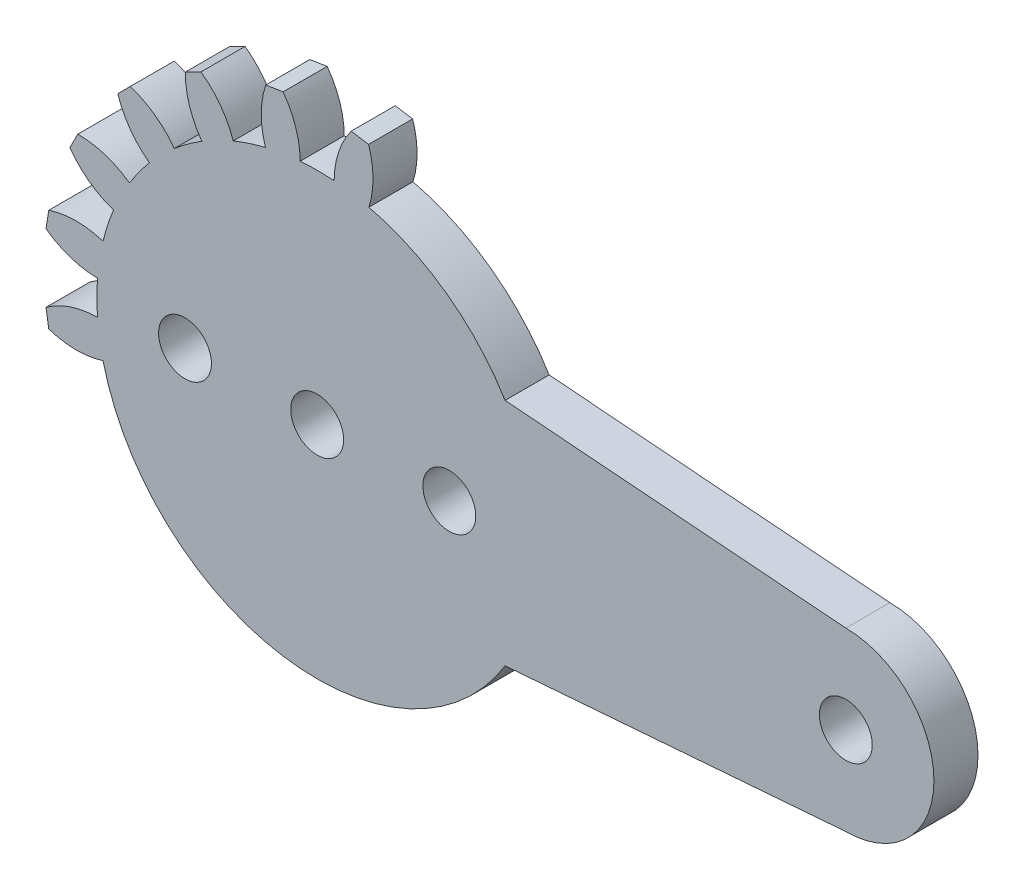
SolidWorks part; units mm, degrees
ref_plane "Front Plane" through (0, 0, 0) normal (0, 0, 1) x (1, 0, 0)
ref_plane "Top Plane" through (0, 0, 0) normal (0, 1, 0) x (1, 0, 0)
ref_plane "Right Plane" through (0, 0, 0) normal (1, 0, 0) x (0, 0, -1)
sketch "Sketch1" plane through (0, 0, 0) normal (0, 0, 1) x (1, 0, 0)
  line L0 (0, 0) -> (30, 0) construction
  line L1 (30, 5) -> (10.6638, 6.5218)
  line L2 (10.6638, 6.5218) -> (-2.4545, 7.5542) construction
  line L3 (-9.5123, 8.1097) -> (-9.5263, 8.1108) construction
  line L4 (30, -5) -> (10.6638, -6.5218)
  line L5 (0, 0) -> (-12.5, 0) construction
  line L6 (0, 0) -> (0, -12.5) construction
  line L7 (0, 0) -> (-4.7898, 14.7414) construction
  line L8 (0, 0) -> (0, 14) construction
  line L9 (0, 0) -> (-2.4247, 15.3092) construction
  line L10 (-2.9186, 15.231) -> (-1.9309, 15.3874)
  line L11 (1.9309, 15.3874) -> (2.9186, 15.231)
  line L12 (6.5913, 14.0376) -> (7.4824, 13.5836) [skipped]
  line L13 (10.6066, 11.3137) -> (11.3137, 10.6066) [skipped]
  line L14 (13.5836, 7.4824) -> (14.0376, 6.5913) [skipped]
  line L15 (15.231, 2.9186) -> (15.3874, 1.9309) [skipped]
  line L16 (15.3874, -1.9309) -> (15.231, -2.9186) [skipped]
  line L17 (14.0376, -6.5913) -> (13.5836, -7.4824) [skipped]
  line L18 (11.3137, -10.6066) -> (10.6066, -11.3137) [skipped]
  line L19 (7.4824, -13.5836) -> (6.5913, -14.0376) [skipped]
  line L20 (2.9186, -15.231) -> (1.9309, -15.3874) [skipped]
  line L21 (-1.9309, -15.3874) -> (-2.9186, -15.231) [skipped]
  line L22 (-6.5913, -14.0376) -> (-7.4824, -13.5836) [skipped]
  line L23 (-10.6066, -11.3137) -> (-11.3137, -10.6066) [skipped]
  line L24 (-13.5836, -7.4824) -> (-14.0376, -6.5913) [skipped]
  line L25 (-15.231, -2.9186) -> (-15.3874, -1.9309)
  line L26 (-15.3874, 1.9309) -> (-15.231, 2.9186)
  line L27 (-14.0376, 6.5913) -> (-13.5836, 7.4824)
  line L28 (-11.3137, 10.6066) -> (-10.6066, 11.3137)
  line L29 (-7.4824, 13.5836) -> (-6.5913, 14.0376)
  line L30 (-2.4545, 7.5542) -> (-9.5123, 8.1097) construction
  line L31 (-9.5263, 8.1108) -> (-11.3101, 8.2512) construction
  line L32 (-11.3101, 8.2512) -> (-26.6541, 9.4588) construction
  arc A0 (-12.1503, -2.9361) -> (10.6638, -6.5218) centre (0, 0) ccw
  circle A1 centre (30, 0) radius 1.5
  circle A2 centre (0, 0) radius 1.5
  arc A3 (30, -5) -> (30, 5) centre (30, 0) ccw
  circle A4 centre (-7.5, 0) radius 1.5
  circle A5 centre (7.5, 0) radius 1.5
  arc A6 (-15.3799, -1.9254) -> (-15.3799, 1.9254) centre (0, 0) ccw construction
  arc A7 (-10.5802, 9.1684) -> (-11.3101, 8.2512) centre (0, 0) ccw construction
  arc A8 (-2.9361, 12.1503) -> (-2.9186, 15.231) centre (1.8294, 13.6636) cw
  arc A9 (-0.9623, 12.4629) -> (-1.9309, 15.3874) centre (-5.9622, 12.4295) ccw
  arc A10 (2.9361, 12.1503) -> (2.9186, 15.231) centre (-1.8294, 13.6636) ccw
  arc A11 (0.9623, 12.4629) -> (1.9309, 15.3874) centre (5.9622, 12.4295) cw
  arc A12 (6.547, 10.6483) -> (7.4824, 13.5836) centre (2.4824, 13.5602) ccw [skipped]
  arc A13 (4.7664, 11.5556) -> (6.5913, 14.0376) centre (9.5113, 9.9788) cw [skipped]
  arc A14 (9.5171, 8.104) -> (11.3137, 10.6066) centre (6.5512, 12.1294) ccw [skipped]
  arc A15 (8.104, 9.5171) -> (10.6066, 11.3137) centre (12.1294, 6.5512) cw [skipped]
  arc A16 (11.5556, 4.7664) -> (14.0376, 6.5913) centre (9.9788, 9.5113) ccw [skipped]
  arc A17 (10.6483, 6.547) -> (13.5836, 7.4824) centre (13.5602, 2.4824) cw [skipped]
  arc A18 (12.4629, 0.9623) -> (15.3874, 1.9309) centre (12.4295, 5.9622) ccw [skipped]
  arc A19 (12.1503, 2.9361) -> (15.231, 2.9186) centre (13.6636, -1.8294) cw [skipped]
  arc A20 (12.1503, -2.9361) -> (15.231, -2.9186) centre (13.6636, 1.8294) ccw [skipped]
  arc A21 (12.4629, -0.9623) -> (15.3874, -1.9309) centre (12.4295, -5.9622) cw [skipped]
  arc A22 (10.6483, -6.547) -> (13.5836, -7.4824) centre (13.5602, -2.4824) ccw [skipped]
  arc A23 (11.5556, -4.7664) -> (14.0376, -6.5913) centre (9.9788, -9.5113) cw [skipped]
  arc A24 (8.104, -9.5171) -> (10.6066, -11.3137) centre (12.1294, -6.5512) ccw [skipped]
  arc A25 (9.5171, -8.104) -> (11.3137, -10.6066) centre (6.5512, -12.1294) cw [skipped]
  arc A26 (4.7664, -11.5556) -> (6.5913, -14.0376) centre (9.5113, -9.9788) ccw [skipped]
  arc A27 (6.547, -10.6483) -> (7.4824, -13.5836) centre (2.4824, -13.5602) cw [skipped]
  arc A28 (0.9623, -12.4629) -> (1.9309, -15.3874) centre (5.9622, -12.4295) ccw [skipped]
  arc A29 (2.9361, -12.1503) -> (2.9186, -15.231) centre (-1.8294, -13.6636) cw [skipped]
  arc A30 (-2.9361, -12.1503) -> (-2.9186, -15.231) centre (1.8294, -13.6636) ccw [skipped]
  arc A31 (-0.9623, -12.4629) -> (-1.9309, -15.3874) centre (-5.9622, -12.4295) cw [skipped]
  arc A32 (-6.547, -10.6483) -> (-7.4824, -13.5836) centre (-2.4824, -13.5602) ccw [skipped]
  arc A33 (-4.7664, -11.5556) -> (-6.5913, -14.0376) centre (-9.5113, -9.9788) cw [skipped]
  arc A34 (-9.5171, -8.104) -> (-11.3137, -10.6066) centre (-6.5512, -12.1294) ccw [skipped]
  arc A35 (-8.104, -9.5171) -> (-10.6066, -11.3137) centre (-12.1294, -6.5512) cw [skipped]
  arc A36 (-11.5556, -4.7664) -> (-14.0376, -6.5913) centre (-9.9788, -9.5113) ccw [skipped]
  arc A37 (-10.6483, -6.547) -> (-13.5836, -7.4824) centre (-13.5602, -2.4824) cw [skipped]
  arc A38 (-12.4629, -0.9623) -> (-15.3874, -1.9309) centre (-12.4295, -5.9622) ccw
  arc A39 (-12.1503, -2.9361) -> (-15.231, -2.9186) centre (-13.6636, 1.8294) cw
  arc A40 (-12.1503, 2.9361) -> (-15.231, 2.9186) centre (-13.6636, -1.8294) ccw
  arc A41 (-12.4629, 0.9623) -> (-15.3874, 1.9309) centre (-12.4295, 5.9622) cw
  arc A42 (-10.6483, 6.547) -> (-13.5836, 7.4824) centre (-13.5602, 2.4824) ccw
  arc A43 (-11.5556, 4.7664) -> (-14.0376, 6.5913) centre (-9.9788, 9.5113) cw
  arc A44 (-8.104, 9.5171) -> (-10.6066, 11.3137) centre (-12.1294, 6.5512) ccw
  arc A45 (-9.5171, 8.104) -> (-11.3137, 10.6066) centre (-6.5512, 12.1294) cw
  arc A46 (-4.7664, 11.5556) -> (-6.5913, 14.0376) centre (-9.5113, 9.9788) ccw
  arc A47 (-6.547, 10.6483) -> (-7.4824, 13.5836) centre (-2.4824, 13.5602) cw
  arc A48 (-12.4629, -0.9623) -> (-12.1503, -2.9361) centre (0, 0) ccw construction
  arc A49 (-12.1503, 2.9361) -> (-12.4629, 0.9623) centre (0, 0) ccw construction
  arc A50 (-12.4629, 0.9623) -> (-12.4629, -0.9623) centre (0, 0) ccw
  arc A51 (-10.6483, 6.547) -> (-11.5556, 4.7664) centre (0, 0) ccw construction
  arc A52 (-11.5556, 4.7664) -> (-12.1503, 2.9361) centre (0, 0) ccw
  arc A53 (-8.104, 9.5171) -> (-9.5123, 8.1097) centre (0, 0) ccw construction
  arc A54 (-9.5171, 8.104) -> (-10.6483, 6.547) centre (0, 0) ccw
  arc A55 (-4.7664, 11.5556) -> (-6.547, 10.6483) centre (0, 0) ccw construction
  arc A56 (-6.547, 10.6483) -> (-8.104, 9.5171) centre (0, 0) ccw
  arc A57 (-1.9554, 12.3461) -> (-2.9361, 12.1503) centre (0, 0) ccw construction
  arc A58 (-2.9361, 12.1503) -> (-4.7664, 11.5556) centre (0, 0) ccw
  arc A59 (2.9361, 12.1503) -> (0.9623, 12.4629) centre (0, 0) ccw construction
  arc A60 (0.9623, 12.4629) -> (-0.9623, 12.4629) centre (0, 0) ccw
  arc A61 (-7.2292, 11.9891) -> (-9.1684, 10.5802) centre (0, 0) ccw construction
  arc A62 (-9.1684, 10.5802) -> (-10.5802, 9.1684) centre (0, 0) ccw construction
  arc A63 (-11.3101, 8.2512) -> (-11.9891, 7.2292) centre (0, 0) ccw construction
  arc A64 (-13.6363, 3.1705) -> (-13.9486, 1.1985) centre (0, 0) ccw construction
  arc A65 (-11.9891, 7.2292) -> (-12.8956, 5.4502) centre (0, 0) ccw construction
  arc A66 (-13.9486, 1.1985) -> (-13.9486, -1.1985) centre (0, 0) ccw construction
  arc A67 (-13.9486, -1.1985) -> (-13.6363, -3.1705) centre (0, 0) ccw construction
  arc A68 (-15.3799, 1.9254) -> (-15.3799, -1.9254) centre (0, 0) ccw construction
  arc A69 (-13.6363, -3.1705) -> (12.4616, -6.3803) centre (0, 0) ccw construction
  arc A70 (-2.1901, 13.8276) -> (-3.1705, 13.6363) centre (0, 0) ccw construction
  arc A71 (12.4616, -6.3803) -> (14, 0) centre (0, 0) ccw construction
  arc A72 (10.6638, -6.5218) -> (12.5, 0) centre (0, 0) ccw construction
  arc A73 (10.6638, 6.5218) -> (2.9361, 12.1503) centre (0, 0) ccw
  arc A74 (14, 0) -> (12.4616, 6.3803) centre (0, 0) ccw construction
  arc A75 (12.4616, 6.3803) -> (3.1705, 13.6363) centre (0, 0) ccw construction
  arc A76 (3.1705, 13.6363) -> (1.1985, 13.9486) centre (0, 0) ccw construction
  arc A77 (1.1985, 13.9486) -> (0, 14) centre (0, 0) ccw construction
  arc A78 (0, 14) -> (-1.1985, 13.9486) centre (0, 0) ccw construction
  arc A79 (-1.1985, 13.9486) -> (-2.1901, 13.8276) centre (0, 0) ccw construction
  arc A80 (-0.9623, 12.4629) -> (-1.9554, 12.3461) centre (0, 0) ccw construction
  arc A81 (-3.1705, 13.6363) -> (-4.3262, 13.3148) centre (0, 0) ccw construction
  arc A82 (-5.4502, 12.8956) -> (-7.2292, 11.9891) centre (0, 0) ccw construction
  arc A83 (-4.3262, 13.3148) -> (-5.4502, 12.8956) centre (0, 0) ccw construction
  arc A84 (12.5, 0) -> (10.6638, 6.5218) centre (0, 0) ccw construction
  arc A85 (-9.5123, 8.1097) -> (-9.5171, 8.104) centre (0, 0) ccw construction
  arc A86 (-12.8956, 5.4502) -> (-13.6363, 3.1705) centre (0, 0) ccw construction
  arc A87 (25, 0) -> (30, -5) centre (30, 0) ccw construction
  arc A88 (30, 5) -> (25, 0) centre (30, 0) ccw construction
  point P21 (-1.9554, 12.3461)
  point P27 (-2.4247, 15.3092)
  point P149 (0, 0)
  dimension "D1" = 25
  dimension "D2" = 3
  dimension "D3" = 10
  dimension "D5" = 3
  dimension "D7" = 31
  dimension "D8" = 28
  dimension "D13" = 5
  dimension "30" = 30
  dimension "D4" = 4.5
  dimension "D6" = 7.5
  dimension "D9" = 18
  dimension "D10" = 9
  dimension "D11" = 1
  dimension "D12" = 1
  dimension "D14" = 20
extrude "Boss-Extrude1" add sketch "Sketch1" along normal blind 2.5
sketch "Sketch2" plane through (0, 0, 2.5) normal (0, 0, 1) x (1, 0, 0)
  circle A0 centre (0, 0) radius 15.5 construction
